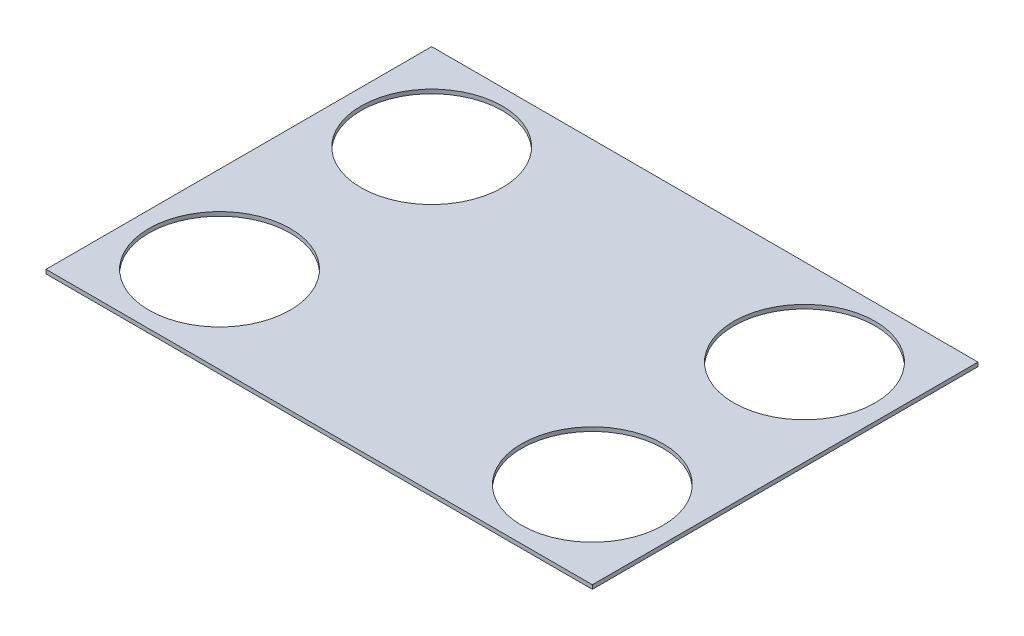
SolidWorks part; units mm, degrees
ref_plane "Front Plane" through (0, 0, 0) normal (0, 0, 1) x (1, 0, 0)
ref_plane "Top Plane" through (0, 0, 0) normal (0, 1, 0) x (1, 0, 0)
ref_plane "Right Plane" through (0, 0, 0) normal (1, 0, 0) x (0, 0, -1)
sketch "Sketch1" plane through (0, 0, 0) normal (0, 1, 0) x (1, 0, 0)
  line L1 (0, 0) -> (431.8, 0)
  line L2 (0, 0) -> (0, 304.8)
  line L3 (0, 304.8) -> (431.8, 304.8)
  line L4 (431.8, 0) -> (431.8, 304.8)
  circle A0 centre (68.58, 68.58) radius 55.88
  circle A1 centre (363.22, 68.58) radius 55.88
  circle A3 centre (363.22, 236.22) radius 55.88
  circle A5 centre (68.58, 236.22) radius 55.88
  dimension "D3" = 111.76
  dimension "D4" = 12.7
  dimension "D5" = 12.7
  dimension "D1" = 55.88
  dimension "D2" = 182.88
  dimension "D8" = 12.7
  dimension "D9" = 12.7
  dimension "D10" = 304.8
  dimension "D11" = 431.8
extrude "Boss-Extrude1" add sketch "Sketch1" along normal blind 3.175
